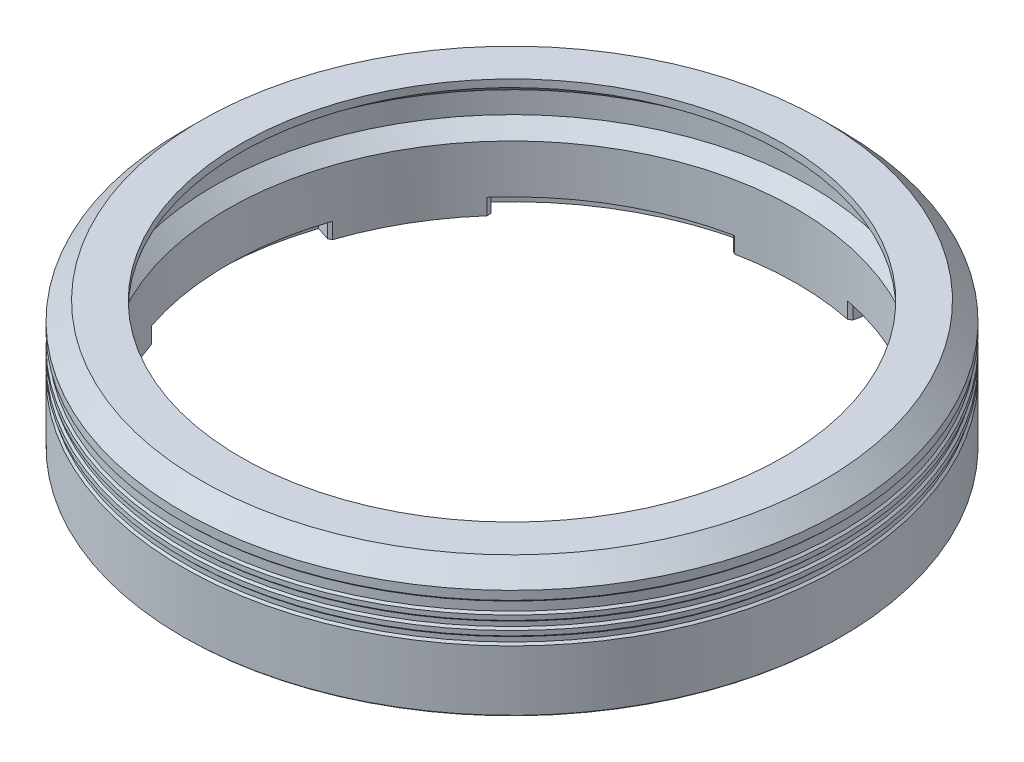
SolidWorks part; units mm, degrees
material "1060 合金"
ref_plane "前视基准面" through (0, 0, 0) normal (0, 0, 1) x (1, 0, 0)
ref_plane "上视基准面" through (0, 0, 0) normal (0, 1, 0) x (1, 0, 0)
ref_plane "右视基准面" through (0, 0, 0) normal (1, 0, 0) x (0, 0, -1)
sketch "草图1" plane through (0, 0, 0) normal (0, 0, 1) x (1, 0, 0)
  line L0 (0, 0) -> (-12.8351, 0) construction
  line L1 (-21.3, 0) -> (-21.3, 0.55)
  line L2 (-21.3, 0.55) -> (-20.3, 0.55)
  line L3 (-20.3, 0.55) -> (-20.3, 1.11)
  line L4 (-20.3, 1.11) -> (-23.3, 1.11)
  line L5 (-23.3, 1.11) -> (-24.65, -0.24)
  line L6 (-24.65, -0.24) -> (-24.65, -0.89)
  line L7 (-24.65, -8.435) -> (-21.3, -8.435)
  line L12 (0, 0.2665) -> (0, 12.2452) construction
  line L17 (-21.3, 0) -> (-22.3, -1)
  line L18 (-22.3, -1) -> (-22.3, -2.615)
  line L19 (-22.3, -2.615) -> (-21.3, -3.615)
  line L20 (-21.3, -3.615) -> (-21.3, -8.435)
  line L21 (-24.65, -0.89) -> (-24.5, -1.04)
  line L22 (-24.5, -1.04) -> (-24.5, -1.69)
  line L23 (-24.5, -1.69) -> (-24.65, -1.84)
  line L24 (-24.65, -2.19) -> (-24.5, -2.34)
  line L25 (-24.5, -2.34) -> (-24.5, -2.69)
  line L26 (-24.5, -2.69) -> (-24.65, -2.84)
  line L28 (-24.65, -3.19) -> (-24.5, -3.34)
  line L29 (-24.5, -3.34) -> (-24.5, -3.69)
  line L30 (-24.5, -3.69) -> (-24.65, -3.84)
  line L31 (-24.65, -1.84) -> (-24.65, -2.19)
  line L32 (-24.65, -2.84) -> (-24.65, -3.19)
  line L33 (-24.65, -3.84) -> (-24.65, -8.435)
  point P16 (-20.8, 0.55)
  point P28 (0, 0)
  point P30 (-24.4265, -3.7503)
  point P31 (-24.65, -2.24)
  point P32 (0, 0)
  point P33 (0, 0)
  dimension "D1" = 42.6
  dimension "D2" = 40.6
  dimension "D3" = 0.56
  dimension "D4" = 0.55
  dimension "D5" = 45
  dimension "D6" = 3.35
  dimension "D7" = 3
  dimension "D8" = 9.545
  dimension "D9" = 45
  dimension "D10" = 45
  dimension "D11" = 4.82
  dimension "D12" = 1
  dimension "D13" = 45
  dimension "D14" = 0.15
  dimension "D15" = 0.35
  dimension "D19" = 0.65
revolve "旋转1" add sketch "草图1" angle 360 about L12
sketch "草图2" plane through (0, -8.435, 0) normal (0, -1, 0) x (1, 0, 0)
  line L0 (0, 0) -> (0, -50000) construction
  line L1 (0, 0) -> (43301.2702, 25000) construction
  line L2 (0, 0) -> (-43301.2702, 25000) construction
  line L3 (0, 21.3) -> (0, 24.6) construction
  line L4 (0, 0) -> (33.6187, 0) construction
  circle A0 centre (0, 0) radius 22.95 construction
  circle A1 centre (19.8753, 11.475) radius 1.55
  circle A2 centre (0, 0) radius 24.65
  circle A4 centre (19.8753, -11.475) radius 1.55
  circle A5 centre (0, 0) radius 21.3 construction
  circle A6 centre (-19.8753, -11.475) radius 1.55
  circle A7 centre (-19.8753, 11.475) radius 1.55
  circle A8 centre (0, 22.95) radius 1.55
  circle A9 centre (0, -22.95) radius 1.55
  circle A11 centre (0, 0) radius 24.65 construction
  point P15 (0, 22.95)
  dimension "D3" = 0
  dimension "D4" = 3.1
  dimension "D5" = 45.9
  dimension "D1" = 60
  dimension "D2" = 60
extrude "切除-拉伸1" cut sketch "草图2" against normal blind 4
sketch "草图3" plane through (0, -8.435, 0) normal (0, -1, 0) x (1, 0, 0)
  line L0 (0, 0) -> (0, 50000) construction
  line L1 (0, 0) -> (43301.2702, 25000) construction
  line L2 (0, 0) -> (43301.2702, -25000) construction
  line L3 (-16.7579, 15.0889) -> (-15.829, 14.2525)
  line L4 (-4.6884, 22.0572) -> (-4.4285, 20.8345)
  line L5 (4.6884, 22.0572) -> (4.4285, 20.8345)
  line L6 (16.7579, 15.0889) -> (15.829, 14.2525)
  line L7 (16.7579, -15.0889) -> (15.829, -14.2525)
  line L8 (4.6884, -22.0572) -> (4.4285, -20.8345)
  line L9 (21.4463, 6.9683) -> (20.2575, 6.5821)
  line L10 (21.4463, -6.9683) -> (20.2575, -6.5821)
  line L11 (-21.4463, -6.9683) -> (-20.2575, -6.5821)
  line L12 (-21.4463, 6.9683) -> (-20.2575, 6.5821)
  line L13 (-4.6884, -22.0572) -> (-4.4285, -20.8345)
  line L14 (-16.7579, -15.0889) -> (-15.829, -14.2525)
  line L17 (-2, -23.2) -> (2, -23.2)
  line L18 (-2, -23.2) -> (-2, -22.7)
  line L19 (-2, -22.7) -> (2, -22.7)
  line L20 (2, -23.2) -> (2, -22.7)
  line L21 (-2, -23.2) -> (2, -22.7) construction
  line L22 (-2, -22.7) -> (2, -23.2) construction
  circle A0 centre (0, 0) radius 21.3 construction
  circle A1 centre (0, 0) radius 21.3 construction
  arc A2 (-16.7579, 15.0889) -> (-4.6884, 22.0572) centre (0, 0) cw
  arc A3 (-15.829, 14.2525) -> (-4.4285, 20.8345) centre (0, 0) cw
  arc A4 (15.829, 14.2525) -> (4.4285, 20.8345) centre (0, 0) ccw
  arc A5 (16.7579, 15.0889) -> (4.6884, 22.0572) centre (0, 0) ccw
  arc A6 (4.4285, -20.8345) -> (15.829, -14.2525) centre (0, 0) ccw
  arc A7 (4.6884, -22.0572) -> (16.7579, -15.0889) centre (0, 0) ccw
  arc A8 (21.4463, 6.9683) -> (21.4463, -6.9683) centre (0, 0) cw
  arc A9 (20.2575, 6.5821) -> (20.2575, -6.5821) centre (0, 0) cw
  arc A10 (-20.2575, 6.5821) -> (-20.2575, -6.5821) centre (0, 0) ccw
  arc A11 (-21.4463, 6.9683) -> (-21.4463, -6.9683) centre (0, 0) ccw
  arc A12 (-4.6884, -22.0572) -> (-16.7579, -15.0889) centre (0, 0) cw
  arc A13 (-4.4285, -20.8345) -> (-15.829, -14.2525) centre (0, 0) cw
  point P17 (0, -22.95)
  dimension "D3" = 1.25
  dimension "D1" = 12
  dimension "D2" = 12
  dimension "D4" = 4
  dimension "D5" = 0.5
extrude "切除-拉伸2" cut sketch "草图3" against normal blind 1.2
chamfer "倒角1" distance 0.2 angle 45 12 edges at (4.4285, -7.835, -20.8345) (-4.4285, -7.835, -20.8345) (15.829, -7.835, -14.2525) (20.2575, -7.835, -6.5821) (15.829, -7.835, 14.2525) (-20.2575, -7.835, -6.5821) (-15.829, -7.835, -14.2525) (20.2575, -7.835, 6.5821) (4.4285, -7.835, 20.8345) (-4.4285, -7.835, 20.8345) (-15.829, -7.835, 14.2525) (-20.2575, -7.835, 6.5821)
chamfer "倒角2" distance 0.1 angle 45 1 edges at (0, -8.435, -24.65)
